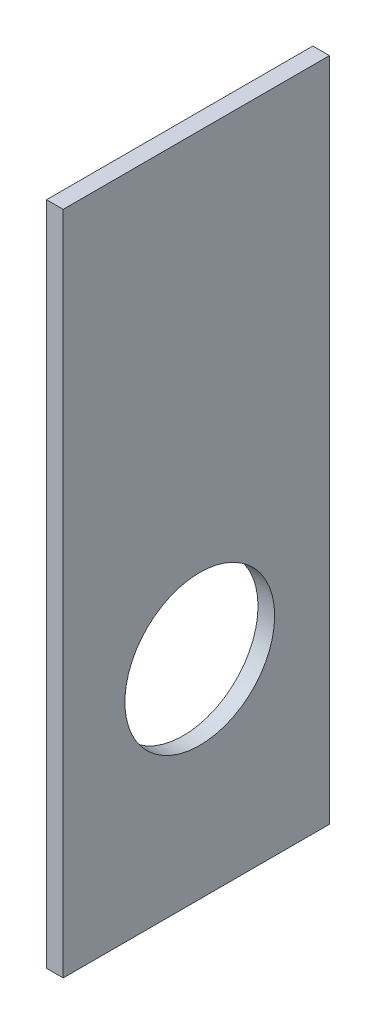
SolidWorks part; units mm, degrees
ref_plane "Front Plane" through (0, 0, 0) normal (0, 0, 1) x (1, 0, 0)
ref_plane "Top Plane" through (0, 0, 0) normal (0, 1, 0) x (1, 0, 0)
ref_plane "Right Plane" through (0, 0, 0) normal (1, 0, 0) x (0, 0, -1)
sketch "Sketch1" plane through (0, 0, 0) normal (1, 0, 0) x (0, 0, -1)
  line L1 (0, 0) -> (50.8, 0)
  line L2 (0, 0) -> (0, 127)
  line L3 (0, 127) -> (50.8, 127)
  line L4 (50.8, 0) -> (50.8, 127)
  dimension "D1" = 50.8
  dimension "D2" = 127
extrude "Boss-Extrude1" add sketch "Sketch1" along normal blind 3.175
sketch "Sketch2" plane through (3.175, 0, 0) normal (1, 0, 0) x (0, 0, -1)
  line L0 (0, 0) -> (50.8, 0) construction
  circle A0 centre (26.0584, 39.6875) radius 14.2875
  dimension "D2" = 28.575
  dimension "D1" = 39.6875
extrude "Cut-Extrude1" cut sketch "Sketch2" against normal blind 9.525
